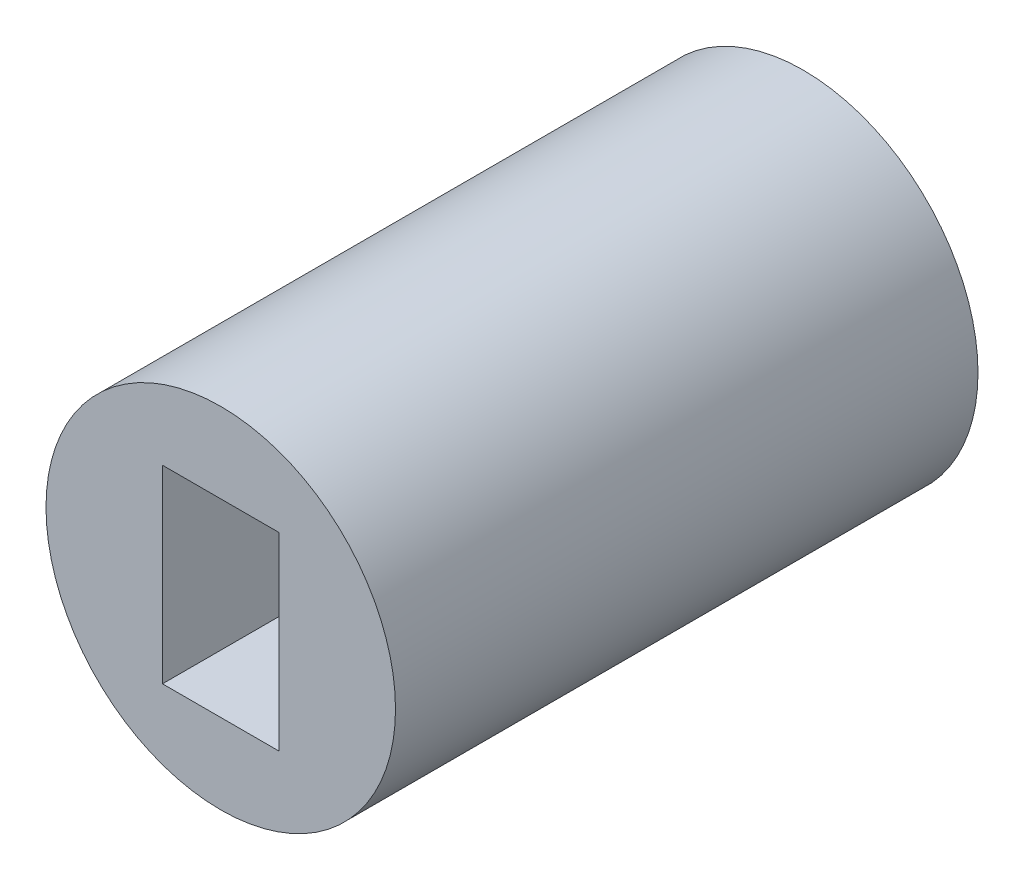
SolidWorks part; units mm, degrees
ref_plane "Plan de face" through (0, 0, 0) normal (0, 0, 1) x (1, 0, 0)
ref_plane "Plan de dessus" through (0, 0, 0) normal (0, 1, 0) x (1, 0, 0)
ref_plane "Plan de droite" through (0, 0, 0) normal (1, 0, 0) x (0, 0, -1)
sketch "Esquisse1" plane through (0, 0, 0) normal (0, 0, 1) x (1, 0, 0)
  circle A0 centre (0, 0) radius 6
extrude "Extrusion1" add sketch "Esquisse1" along normal blind 20
sketch "Esquisse2" plane through (0, 0, 0) normal (0, 0, -1) x (-1, 0, 0)
  line L1 (-2, 3.25) -> (2, 3.25)
  line L2 (-2, 3.25) -> (-2, -3.25)
  line L3 (-2, -3.25) -> (2, -3.25)
  line L4 (2, 3.25) -> (2, -3.25)
  line L5 (-2, 3.25) -> (2, -3.25) construction
  line L6 (-2, -3.25) -> (2, 3.25) construction
  point P0 (0, 0)
extrude "Extrusion2" cut sketch "Esquisse2" against normal blind 20
